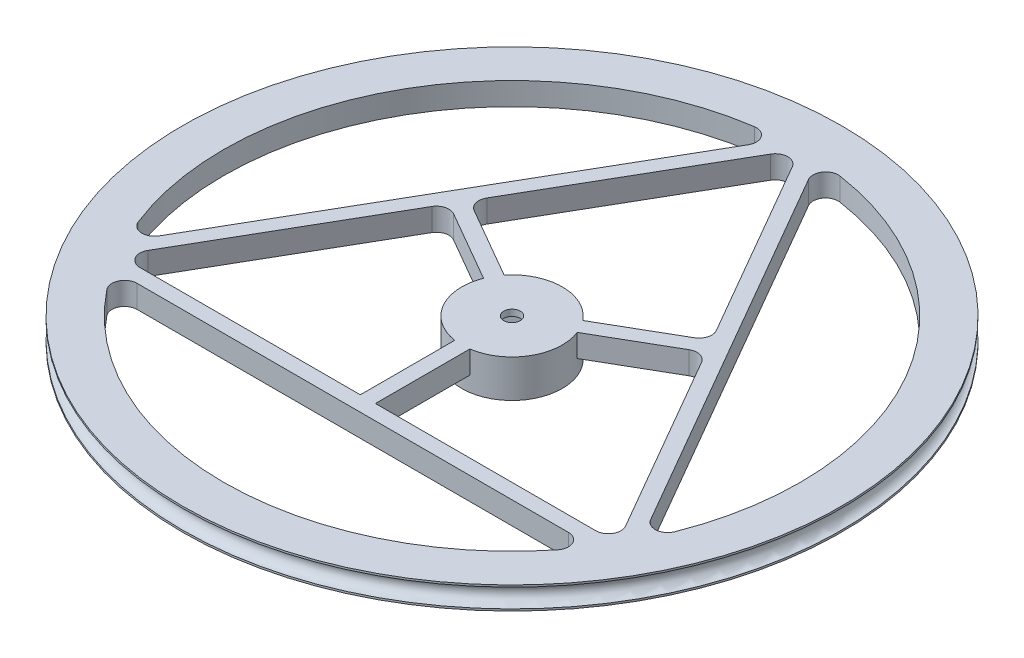
SolidWorks part; units mm, degrees
ref_plane "Front Plane" through (0, 0, 0) normal (0, 0, 1) x (1, 0, 0)
ref_plane "Top Plane" through (0, 0, 0) normal (0, 1, 0) x (1, 0, 0)
ref_plane "Right Plane" through (0, 0, 0) normal (1, 0, 0) x (0, 0, -1)
sketch "Sketch1" plane through (0, 0, 0) normal (0, 1, 0) x (1, 0, 0)
  line L0 (7.9373, 6.3423) -> (22.2492, 14.6054)
  line L1 (9.4613, 3.7027) -> (23.7732, 11.9657)
  line L2 (-7.9373, 6.3423) -> (-22.2492, 14.6054)
  line L3 (-9.4613, 3.7027) -> (-23.7732, 11.9657)
  line L4 (1.524, -10.045) -> (1.524, -29.1111)
  line L5 (-1.524, -10.045) -> (-1.524, -29.1111)
  line L6 (0, 0) -> (9.7887, 5.6515) construction
  line L7 (0, 0) -> (-9.7887, 5.6515) construction
  line L8 (0, 0) -> (0, -11.303) construction
  line L9 (-27.2429, 11.036) -> (-48.2221, -25.3011)
  line L10 (23.1789, 18.0751) -> (2.1997, 54.4121)
  line L11 (1.524, -29.1111) -> (46.0224, -29.1111)
  line L18 (-2.1997, 54.4121) -> (-23.1789, 18.0751)
  line L19 (-46.0224, -29.1111) -> (-1.524, -29.1111)
  line L20 (48.2221, -25.3011) -> (27.2429, 11.036)
  line L21 (-6.0763, 53.7937) -> (-49.6248, -21.6346)
  line L22 (-43.5485, -32.1591) -> (43.5485, -32.1591)
  line L23 (49.6248, -21.6346) -> (6.0763, 53.7937)
  circle A0 centre (0, 0) radius 66.548
  arc A1 (27.2429, 11.036) -> (23.7732, 11.9657) centre (25.0432, 9.766) ccw
  arc A2 (22.2492, 14.6054) -> (23.1789, 18.0751) centre (20.9792, 16.8051) ccw
  arc A3 (-46.0224, -29.1111) -> (-48.2221, -25.3011) centre (-46.0224, -26.5711) cw
  arc A4 (-49.6248, -21.6346) -> (-54.1886, -21.2936) centre (-51.8245, -20.3646) cw
  arc A5 (-6.0763, 53.7937) -> (-8.6535, 57.5755) centre (-8.276, 55.0637) ccw
  arc A6 (8.6535, 57.5755) -> (6.0763, 53.7937) centre (8.276, 55.0637) ccw
  arc A7 (54.1886, -21.2936) -> (49.6248, -21.6346) centre (51.8245, -20.3646) cw
  arc A8 (48.2221, -25.3011) -> (46.0224, -29.1111) centre (46.0224, -26.5711) cw
  arc A9 (45.535, -36.2819) -> (43.5485, -32.1591) centre (43.5485, -34.6991) ccw
  arc A10 (-45.535, -36.2819) -> (-43.5485, -32.1591) centre (-43.5485, -34.6991) cw
  arc A11 (-22.2492, 14.6054) -> (-23.1789, 18.0751) centre (-20.9792, 16.8051) cw
  arc A12 (-23.7732, 11.9657) -> (-27.2429, 11.036) centre (-25.0432, 9.766) ccw
  arc A13 (-7.9373, 6.3423) -> (-9.4613, 3.7027) centre (0, 0) ccw
  arc A14 (-2.1997, 54.4121) -> (2.1997, 54.4121) centre (0, 53.1421) cw
  arc A18 (-1.524, -10.045) -> (1.524, -10.045) centre (0, 0) ccw
  arc A19 (9.4613, 3.7027) -> (7.9373, 6.3423) centre (0, 0) ccw
  arc A22 (-8.6535, 57.5755) -> (-54.1886, -21.2936) centre (0, 0) ccw
  arc A23 (-45.535, -36.2819) -> (45.535, -36.2819) centre (0, 0) ccw
  arc A24 (54.1886, -21.2936) -> (8.6535, 57.5755) centre (0, 0) ccw
  point P13 (24.4489, 15.8754)
  point P16 (-50.4218, -29.1111)
  point P18 (-17.4665, -14.351)
  point P21 (-19.5774, -11.303)
  point P24 (17.4665, -14.351)
  point P27 (19.5774, -11.303)
  point P30 (21.1616, -7.951)
  point P33 (0, 22.606)
  point P35 (52.1179, -25.9527)
  point P44 (50.4218, -29.1111)
  point P46 (-10.5507, 4.3317)
  point P49 (48.5346, -32.1591)
  point P55 (-48.5346, -32.1591)
  point P63 (-25.9729, 13.2357)
  point P64 (1.524, -11.303)
  point P68 (0, 58.2221)
  dimension "D2" = 2.54
  dimension "D9" = 3.048
  dimension "D15" = 3.048
  dimension "D3" = 2.54
  dimension "D16" = 3.048
extrude "Boss-Extrude1" add sketch "Sketch1" along normal blind 4.572
sketch "Sketch2" plane through (0, 4.572, 0) normal (0, 1, 0) x (1, 0, 0)
  circle A0 centre (0, 0) radius 10.16
extrude "Boss-Extrude2" add sketch "Sketch2" against normal blind 7.62
sketch "Sketch3" plane through (0, 4.572, 0) normal (0, 1, 0) x (1, 0, 0)
  circle A0 centre (0, 0) radius 1.6764
extrude "Cut-Extrude1" cut sketch "Sketch3" against normal blind 7.62
sketch "Sketch4" plane through (0, -3.048, 0) normal (0, -1, 0) x (1, 0, 0)
  line L1 (0, 6.858) -> (-5.9392, 3.429)
  line L2 (-5.9392, 3.429) -> (-5.9392, -3.429)
  line L3 (-5.9392, -3.429) -> (0, -6.858)
  line L4 (0, -6.858) -> (5.9392, -3.429)
  line L5 (5.9392, -3.429) -> (5.9392, 3.429)
  line L6 (5.9392, 3.429) -> (0, 6.858)
  circle A0 centre (0, 0) radius 5.9392 construction
  dimension "D1" = 6.858
extrude "Cut-Extrude2" cut sketch "Sketch4" against normal blind 6.35
sketch "Sketch5" plane through (0, 0, 0) normal (0, 0, 1) x (1, 0, 0)
  line L1 (0, 4.1142) -> (0, 8.6291) construction
  line L2 (0, 8.6291) -> (0, -8.1457) construction
sketch "Sketch6" plane through (0, 0, 0) normal (1, 0, 0) x (0, 0, -1)
  line L1 (66.548, 0) -> (66.548, 4.572) construction
  circle A0 centre (66.548, 2.286) radius 1.905
revolve "Cut-Revolve1" cut sketch "Sketch6" angle 360 about L2
